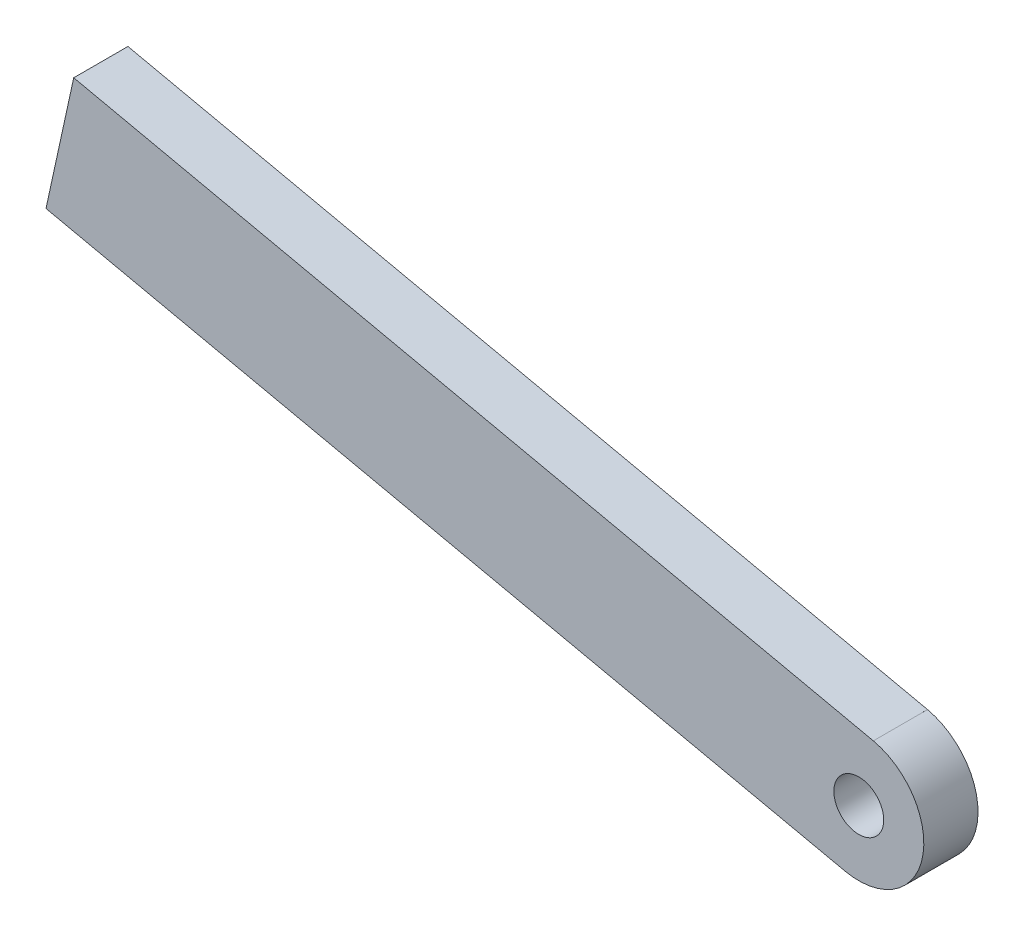
SolidWorks part; units mm, degrees
ref_plane "Front Plane" through (0, 0, 0) normal (0, 0, 1) x (1, 0, 0)
ref_plane "Top Plane" through (0, 0, 0) normal (0, 1, 0) x (1, 0, 0)
ref_plane "Right Plane" through (0, 0, 0) normal (1, 0, 0) x (0, 0, -1)
sketch "Sketch2" plane through (0, 0, 0) normal (0, 0, 1) x (1, 0, 0)
  line L0 (-239.6629, 28.2199) -> (-241.287, 20.775)
  line L1 (-239.6629, 28.2199) -> (-192.8221, 18.001)
  line L2 (-241.287, 20.775) -> (-194.4463, 10.5562)
  line L3 (-192.8221, 18.001) -> (-194.4463, 10.5562)
  circle A0 centre (-193.675, 14.2875) radius 1.4605
  circle A1 centre (-193.675, 14.2875) radius 3.81
extrude "Boss-Extrude1" add sketch "Sketch2" along normal blind 3.175 contours A1 | L1 L3 L2 L0
sketch "Sketch3" plane through (0, 0, 3.175) normal (0, 0, 1) x (1, 0, 0)
  circle A0 centre (-193.675, 14.2875) radius 1.4605
  dimension "D1" = 2.921
extrude "Cut-Extrude1" cut sketch "Sketch3" against normal blind 3.175
